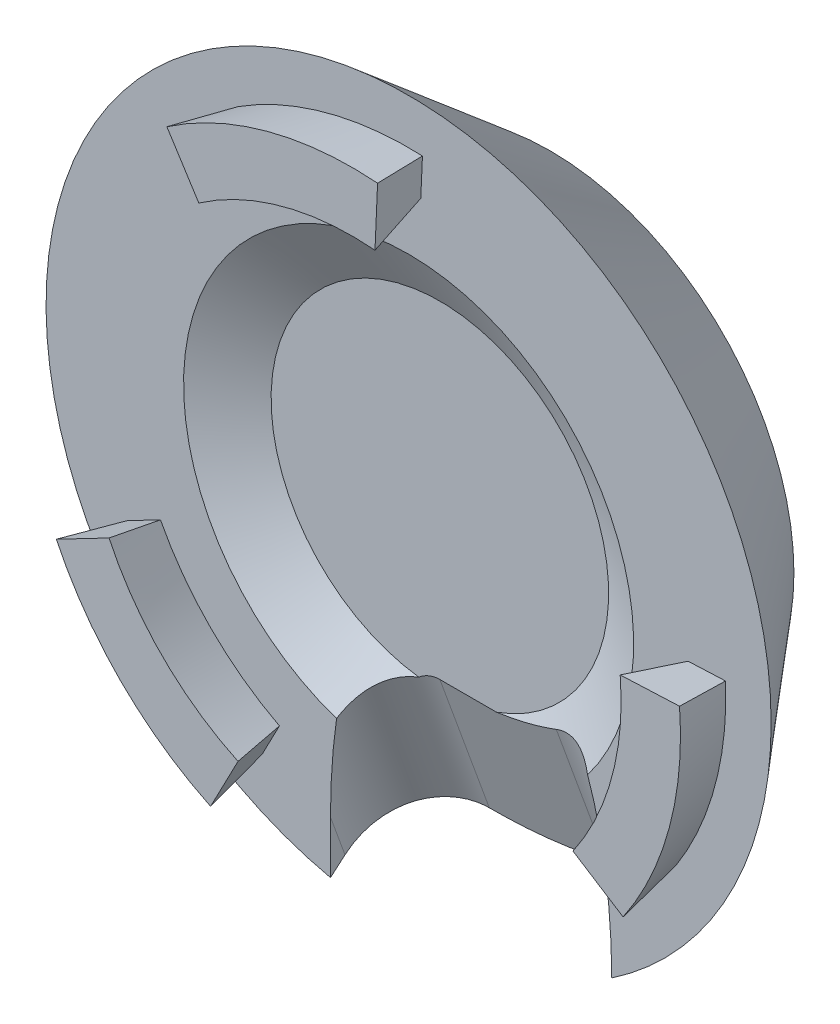
SolidWorks part; units mm, degrees
ref_plane "Front" through (0, 0, 0) normal (0, 0, 1) x (1, 0, 0)
ref_plane "Top" through (0, 0, 0) normal (0, 1, 0) x (1, 0, 0)
ref_plane "Right" through (0, 0, 0) normal (1, 0, 0) x (0, 0, -1)
sketch "Sketch1" plane through (0, 0, 0) normal (1, 0, 0) x (0, 0, -1)
  line L2 (0, 5.8) -> (2.2643, 3.9)
  line L3 (2.2643, 3.9) -> (2.2643, 0)
  line L4 (2.2643, 0) -> (0.5, 0)
  line L5 (0, 3.6) -> (0, 5.8)
  line L7 (2.2643, 3.9) -> (0, 3.9) construction
  line L8 (0, 0) -> (11.2387, 0) construction
  line L15 (0, 3.6) -> (0.5, 2.7)
  line L16 (0.5, 2.7) -> (0.5, 0)
  dimension "D1" = 40
  dimension "D2" = 3.9
  dimension "D3" = 5.8
  dimension "D4" = 0.5
  dimension "D5" = 3.6
  dimension "D6" = 2.7
revolve "Revolve1" add sketch "Sketch1" angle 360 about L8
sketch "Sketch7" plane through (0, 0, 0) normal (0, 0, 1) x (1, 0, 0)
  line L0 (-2.7268, 4.2802) -> (-2.4044, 3.7742)
  line L1 (0.2214, 5.0702) -> (0.1952, 4.4707)
  line L2 (0, 0) -> (5.8, 0) construction
  arc A1 (-2.7268, 4.2802) -> (0.2214, 5.0702) centre (0, 0) cw
  arc A2 (-2.4044, 3.7742) -> (0.1952, 4.4707) centre (0, 0) cw
  circle A3 centre (0, 0) radius 5.8 construction
  point P7 (0.2083, 4.7705)
  dimension "D1" = 35
  dimension "D2" = 0.6
  dimension "D4" = 4.775
  dimension "D3" = 87.5
extrude "Boss-Extrude1" add sketch "Sketch7" along normal blind 0.9 draft 11 contours A1 L1 A2 L0 draft outward yes
pattern_circular "CirPattern1" count 3 over 360 about axis through (0, 0, 0) along (0, 0, 1) of "Boss-Extrude1"
sketch "Sketch8" plane through (0, 0, 0) normal (1, 0, 0) x (0, 0, -1)
  line L0 (0, -6) -> (2.7776, -4.989)
  line L1 (-1.3809, -6) -> (3.438, -6) construction
  dimension "D1" = 20
  dimension "D2" = 6
sketch "Sketch10" plane through (0, 0, 0) normal (0, 0, 1) x (1, 0, 0)
  line L0 (-9.1513, -6) -> (9.1513, -6)
  line L1 (-3.8617, -5.8) -> (7.0958, -5.8)
  circle A1 centre (0, 0) radius 5.8 construction
ref_plane "Plane2" through (0, -5.2981, -1.9284) normal (0, -0.9397, -0.342) x (-1, 0, 0)
sketch "Sketch12" plane through (0, 0, 0) normal (1, 0, 0) x (0, 0, -1)
  line L0 (-0.3556, -4.8229) -> (0.0728, -6)
  line L1 (-0.5765, -6) -> (1.8568, -6) construction
  line L2 (0.0728, -6) -> (1.3921, -5.5198) construction
  dimension "D1" = 20
  dimension "D2" = 6
sketch "Sketch11" plane through (0, -5.2981, -1.9284) normal (0, -0.9397, -0.342) x (-1, 0, 0)
  line L0 (0, -0.4) -> (-2, -0.4)
  line L1 (0, -2.0521) -> (0, 0.9038) construction
  line L2 (0, -2.5938) -> (0, -0.3073) construction
  line L3 (0, -2.9) -> (-2, -2.9)
  line L4 (0, -2.9) -> (1.25, -2.9)
  line L5 (1.25, -2.9) -> (1.25, -1.65)
  line L6 (-2, -2.9) -> (-3.25, -2.9)
  line L7 (-3.25, -2.9) -> (-3.25, -1.65)
  arc A0 (1.25, -1.65) -> (0, -0.4) centre (0, -1.65) ccw
  arc A1 (-2, -0.4) -> (-3.25, -1.65) centre (-2, -1.65) ccw
  ellipse E1 centre (0, 0) end of major axis (-5.8, 0) minor radius 1.9837 construction
  dimension "D1" = 1.25
  dimension "D2" = 1.65
  dimension "D3" = 2
extrude "Cut-Extrude2" cut sketch "Sketch11" against normal up to next contours A0 L0 A1 L7 L6 L3 L4 L5
equation "\"R1\"=4.15"
